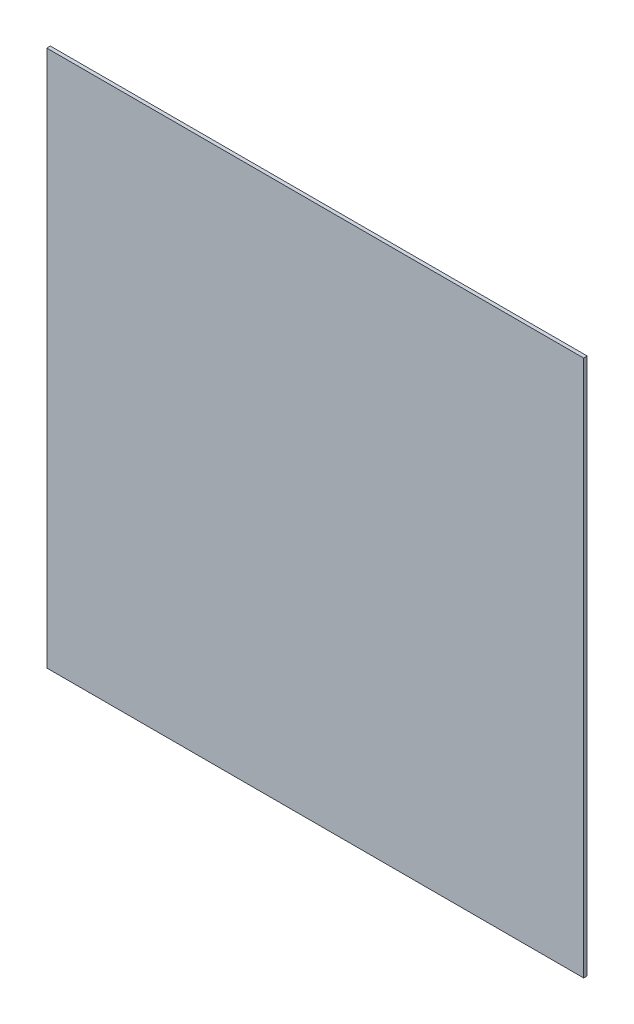
SolidWorks part; units mm, degrees
ref_plane "Спереди" through (0, 0, 0) normal (0, 0, 1) x (1, 0, 0)
ref_plane "Сверху" through (0, 0, 0) normal (0, 1, 0) x (1, 0, 0)
ref_plane "Справа" through (0, 0, 0) normal (1, 0, 0) x (0, 0, -1)
sketch "Эскиз1" plane through (0, 0, 0) normal (0, 0, 1) x (1, 0, 0)
  line L1 (0, 0) -> (150, 0)
  line L2 (0, 0) -> (0, 150)
  line L3 (0, 150) -> (150, 150)
  line L4 (150, 0) -> (150, 150)
  dimension "D1" = 150
  dimension "D2" = 150
extrude "Бобышка-Вытянуть1" add sketch "Эскиз1" along normal blind 1
